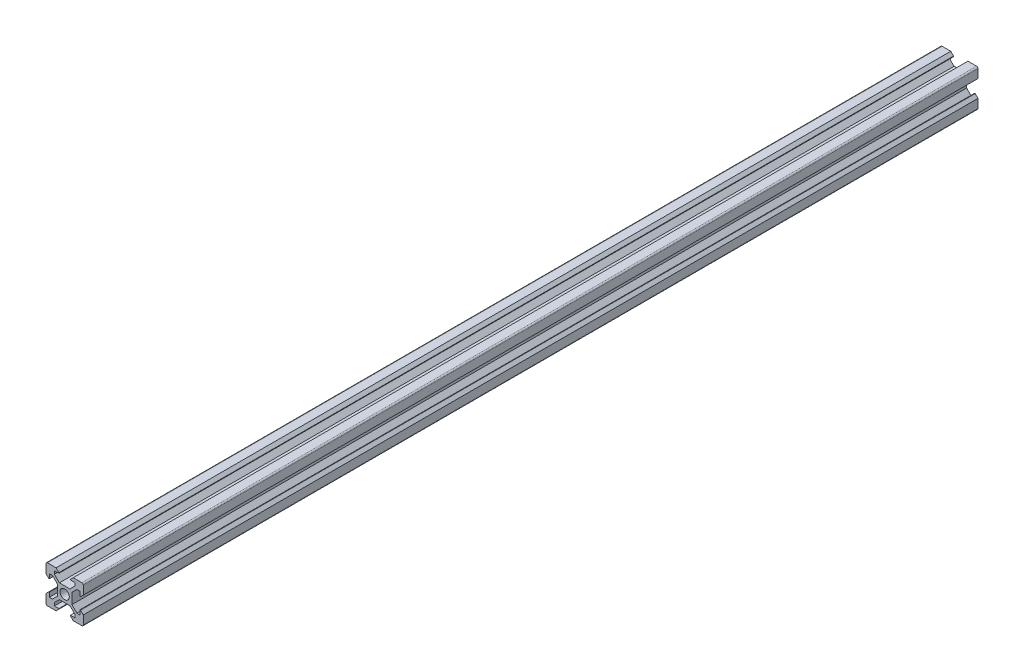
SolidWorks part; units mm, degrees
ref_plane "Alzado" through (0, 0, 0) normal (0, 0, 1) x (1, 0, 0)
ref_plane "Planta" through (0, 0, 0) normal (0, 1, 0) x (1, 0, 0)
ref_plane "Vista lateral" through (0, 0, 0) normal (1, 0, 0) x (0, 0, -1)
sketch "Croquis1" plane through (0, 0, 0) normal (0, 0, 1) x (1, 0, 0)
  line L0 (-4.6, 10) -> (-3.1, 8.5)
  line L3 (-4.6, 10) -> (-9.25, 10)
  line L5 (-3.1, 8.5) -> (-3.1, 8.2)
  line L6 (-3.1, 8.2) -> (-5.5, 8.2)
  line L7 (-5.5, 8.2) -> (-5.5, 6.5607)
  line L8 (-5.5, 6.5607) -> (-2.84, 3.9007)
  line L9 (-2.84, 3.9007) -> (0, 3.9007)
  line L10 (0, 0) -> (-15.3499, 15.3499) construction
  line L11 (-3.9007, 2.84) -> (-3.9007, 0)
  line L12 (-6.5607, 5.5) -> (-3.9007, 2.84)
  line L13 (-8.2, 5.5) -> (-6.5607, 5.5)
  line L14 (-8.2, 3.1) -> (-8.2, 5.5)
  line L15 (-8.5, 3.1) -> (-8.2, 3.1)
  line L16 (-10, 4.6) -> (-10, 9.25)
  line L17 (-10, 4.6) -> (-8.5, 3.1)
  line L18 (10, 4.6) -> (8.5, 3.1)
  line L19 (10, 4.6) -> (10, 9.25)
  line L20 (8.5, 3.1) -> (8.2, 3.1)
  line L21 (8.2, 3.1) -> (8.2, 5.5)
  line L22 (8.2, 5.5) -> (6.5607, 5.5)
  line L23 (6.5607, 5.5) -> (3.9007, 2.84)
  line L24 (3.9007, 2.84) -> (3.9007, 0)
  line L25 (5.5, 6.5607) -> (2.84, 3.9007)
  line L26 (5.5, 8.2) -> (5.5, 6.5607)
  line L27 (3.1, 8.2) -> (5.5, 8.2)
  line L28 (3.1, 8.5) -> (3.1, 8.2)
  line L29 (4.6, 10) -> (9.25, 10)
  line L30 (4.6, 10) -> (3.1, 8.5)
  line L31 (2.84, 3.9007) -> (0, 3.9007)
  line L32 (4.6, -10) -> (3.1, -8.5)
  line L33 (4.6, -10) -> (9.25, -10)
  line L34 (3.1, -8.5) -> (3.1, -8.2)
  line L35 (3.1, -8.2) -> (5.5, -8.2)
  line L36 (5.5, -8.2) -> (5.5, -6.5607)
  line L37 (5.5, -6.5607) -> (2.84, -3.9007)
  line L38 (2.84, -3.9007) -> (0, -3.9007)
  line L39 (6.5607, -5.5) -> (3.9007, -2.84)
  line L40 (8.2, -5.5) -> (6.5607, -5.5)
  line L41 (8.2, -3.1) -> (8.2, -5.5)
  line L42 (8.5, -3.1) -> (8.2, -3.1)
  line L43 (10, -4.6) -> (10, -9.25)
  line L44 (10, -4.6) -> (8.5, -3.1)
  line L45 (3.9007, -2.84) -> (3.9007, 0)
  line L46 (-10, -4.6) -> (-8.5, -3.1)
  line L47 (-10, -4.6) -> (-10, -9.25)
  line L48 (-8.5, -3.1) -> (-8.2, -3.1)
  line L49 (-8.2, -3.1) -> (-8.2, -5.5)
  line L50 (-8.2, -5.5) -> (-6.5607, -5.5)
  line L51 (-6.5607, -5.5) -> (-3.9007, -2.84)
  line L52 (-3.9007, -2.84) -> (-3.9007, 0)
  line L53 (-5.5, -6.5607) -> (-2.84, -3.9007)
  line L54 (-5.5, -8.2) -> (-5.5, -6.5607)
  line L55 (-3.1, -8.2) -> (-5.5, -8.2)
  line L56 (-3.1, -8.5) -> (-3.1, -8.2)
  line L57 (-4.6, -10) -> (-9.25, -10)
  line L58 (-4.6, -10) -> (-3.1, -8.5)
  line L59 (-2.84, -3.9007) -> (0, -3.9007)
  circle A0 centre (0, 0) radius 2.5
  arc A1 (-9.25, 10) -> (-10, 9.25) centre (-9.25, 9.25) ccw
  arc A2 (10, 9.25) -> (9.25, 10) centre (9.25, 9.25) ccw
  arc A3 (9.25, -10) -> (10, -9.25) centre (9.25, -9.25) ccw
  arc A4 (-10, -9.25) -> (-9.25, -10) centre (-9.25, -9.25) ccw
  point P18 (-10, 10)
  point P37 (10, 10)
  point P55 (10, -10)
  point P73 (-10, -10)
  point P79 (0, 0)
  dimension "D1" = 5
  dimension "D5" = 0.75
  dimension "D2" = 10
  dimension "D3" = 10
  dimension "D4" = 4.6
  dimension "D6" = 5.5
  dimension "D7" = 135
  dimension "D8" = 0.75
  dimension "D9" = 225
  dimension "D10" = 2.84
  dimension "D11" = 1.8
  dimension "D12" = 3.1
  dimension "D13" = 4
extrude "Saliente-Extruir1" add sketch "Croquis1" along normal blind 480
